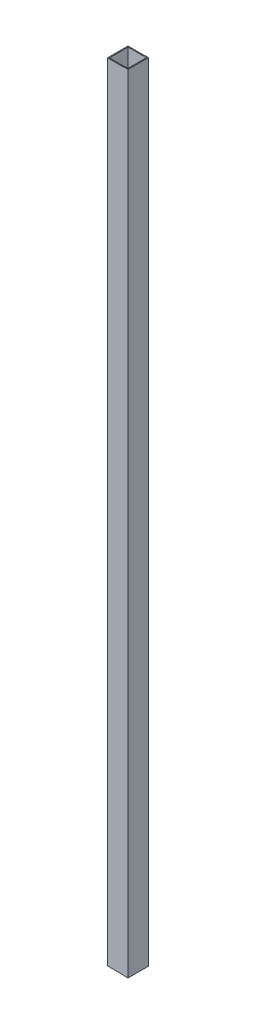
SolidWorks part; units mm, degrees
ref_plane "Front Plane" through (0, 0, 0) normal (0, 0, 1) x (1, 0, 0)
ref_plane "Top Plane" through (0, 0, 0) normal (0, 1, 0) x (1, 0, 0)
ref_plane "Right Plane" through (0, 0, 0) normal (1, 0, 0) x (0, 0, -1)
sketch "Sketch1" plane through (0, 0, 0) normal (0, 1, 0) x (1, 0, 0)
  line L0 (0, 0) -> (0, 50)
  line L1 (0, 50) -> (50, 50)
  line L2 (50, 50) -> (50, 0)
  line L3 (50, 0) -> (0, 0)
  line L4 (2.2, 47.8) -> (47.8, 47.8)
  line L5 (47.8, 47.8) -> (47.8, 2.2)
  line L6 (47.8, 2.2) -> (2.2, 2.2)
  line L7 (2.2, 2.2) -> (2.2, 47.8)
  dimension "D1" = 50
  dimension "D2" = 50
  dimension "D3" = 2.2
extrude "Boss-Extrude1" add sketch "Sketch1" along normal blind 1923
sketch "Sketch2" plane through (0, 0, 0) normal (0, 0, 1) x (1, 0, 0)
  line L0 (0, 0) -> (0, 0.5)
  line L1 (0, 1923) -> (0, 0) construction
  line L2 (0, 0.5) -> (40, 0.5)
  line L3 (40, 0.5) -> (40, 0)
  line L5 (40, 0) -> (0, 0)
  line L6 (0, 1923) -> (40, 1923)
  line L7 (0, 1923) -> (50, 1923) construction
  line L8 (40, 1923) -> (40, 1922.5)
  line L9 (40, 1922.5) -> (0, 1922.5)
  line L10 (0, 1922.5) -> (0, 1923)
  dimension "D1" = 0.5
  dimension "D2" = 40
  dimension "D3" = 0.5
  dimension "D4" = 40
extrude "Cut-Extrude2" cut sketch "Sketch2" against normal blind 50
equation "\"SquareTube_length\"=1923.0"
equation "\"D1@Boss-Extrude1\"=\"SquareTube_length\""
equation "\"SquareTube_inFront1_cutDepth50_R\"=0.5"
equation "\"D1@Sketch2\"=\"SquareTube_inFront1_cutDepth50_R\""
equation "\"SquareTube_inFront1_cutDepth50_L\"=0.5"
equation "\"D3@Sketch2\"=\"SquareTube_inFront1_cutDepth50_L\""
equation "\"CarBeamWidth\"=700.0"
equation "\"MetalSheet_3mm_length\"=5030.0"
equation "\"MetalSheet_3mm_width\"=1923.0"
equation "\"MetalSheet_3mm_FloorCut_L_length\"=1764.0"
equation "\"MetalSheet_3mm_FloorCut_L_disdance\"=1665.0"
equation "\"MetalSheet_3mm_FloorCut_R_length\"=1764.0"
equation "\"MetalSheet_3mm_FloorCut_R_disdance\"=1665.0"
equation "\"indoorHeight\"=1940.0"
equation "\"x\"=66.0"
equation "\"da\"=62.0"
equation "\"SquareTube_wheel_length\"= 750"
equation "\"channelSteel_length\"=5030.0"
equation "\"SquareTube_inFront2_cutDepth50_R\"=0.5"
equation "\"SquareTube_inFront2_cutDepth50_L\"=0.5"
equation "\"SquareTube_inFront3_cutDepth50_R\"=0.5"
equation "\"SquareTube_inFront3_cutDepth50_L\"=0.5"
equation "\"SquareTube_inFront4_cutDepth50_R\"=0.5"
equation "\"SquareTube_inFront4_cutDepth50_L\"=0.5"
equation "\"SquareTube_inFront5_cutDepth50_R\"=50"
equation "\"SquareTube_inFront5_cutDepth50_L\"=50"
equation "\"SquareTube_inFront6_cutDepth50_R\"=50"
equation "\"SquareTube_inFront6_cutDepth50_L\"=50"
equation "\"SquareTube_inFront7_cutDepth50_R\"=50"
equation "\"SquareTube_inFront7_cutDepth50_L\"=50"
equation "\"SquareTube_inFront8_cutDepth50_R\"=50"
equation "\"SquareTube_inFront8_cutDepth50_L\"=50"
equation "\"SquareTube_inFront9_cutDepth50_R\"=50"
equation "\"SquareTube_inFront9_cutDepth50_L\"=50"
equation "\"SquareTube_inFront10_cutDepth50_R\"=50"
equation "\"SquareTube_inFront10_cutDepth50_L\"=50"
equation "\"SquareTube_inBack1_cutDepth50_R\"=50"
equation "\"SquareTube_inBack1_cutDepth50_L\"=50"
equation "\"SquareTube_inBack2_cutDepth50_R\"=50"
equation "\"SquareTube_inBack2_cutDepth50_L\"=50"
equation "\"SquareTube_inBack3_cutDepth50_R\"=50"
equation "\"SquareTube_inBack3_cutDepth50_L\"=50"
equation "\"SquareTube_inBack4_cutDepth50_R\"=50"
equation "\"SquareTube_inBack4_cutDepth50_L\"=50"
equation "\"SquareTube_inBack5_cutDepth50_R\"=50"
equation "\"SquareTube_inBack5_cutDepth50_L\"=50"
equation "\"SquareTube_inBack6_cutDepth50_R\"=0.5"
equation "\"SquareTube_inBack6_cutDepth50_L\"=0.5"
